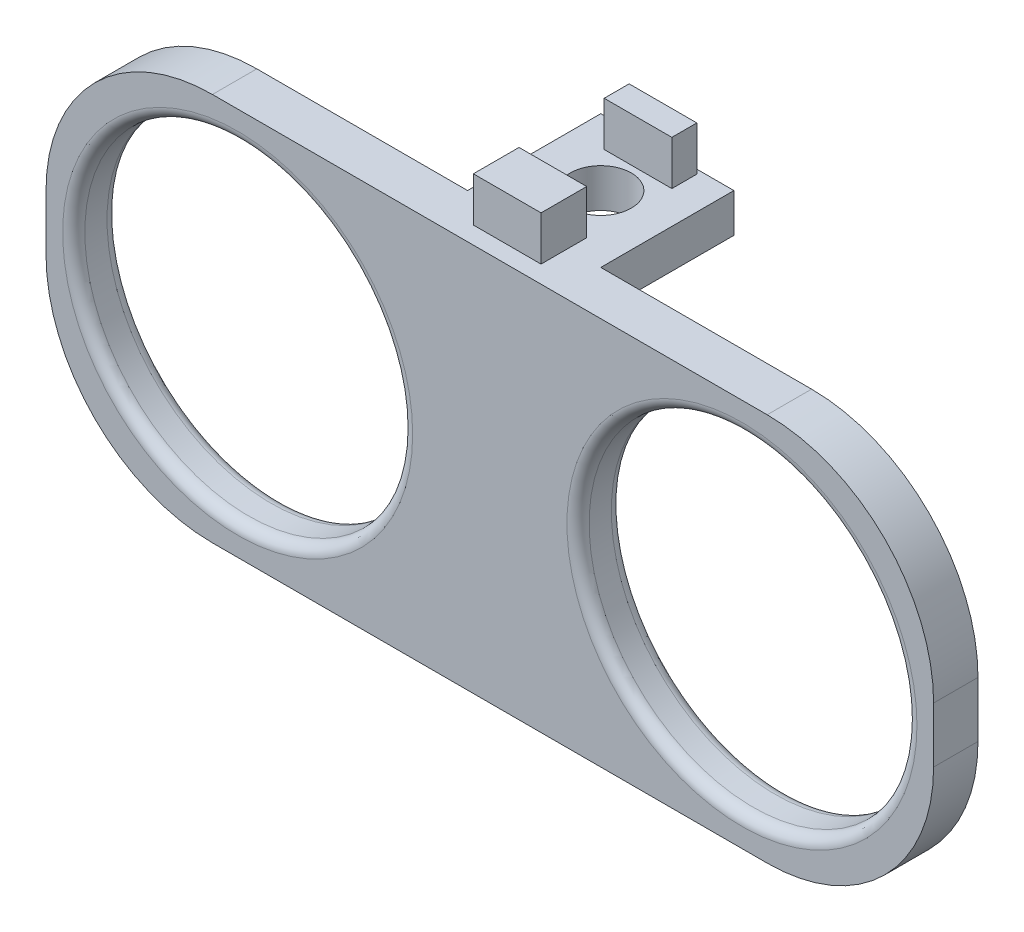
SolidWorks part; units mm, degrees
ref_plane "Front Plane" through (0, 0, 0) normal (0, 0, 1) x (1, 0, 0)
ref_plane "Top Plane" through (0, 0, 0) normal (0, 1, 0) x (1, 0, 0)
ref_plane "Right Plane" through (0, 0, 0) normal (1, 0, 0) x (0, 0, -1)
sketch "Sketch1" plane through (0, 0, 0) normal (0, 0, 1) x (1, 0, 0)
  line L1 (-40, 17.5) -> (40, 17.5)
  line L2 (-40, 17.5) -> (-40, -17.5)
  line L3 (-40, -17.5) -> (40, -17.5)
  line L4 (40, 17.5) -> (40, -17.5)
  line L5 (-40, 17.5) -> (40, -17.5) construction
  line L6 (-40, -17.5) -> (40, 17.5) construction
  point P0 (0, 0)
  dimension "D1" = 80
  dimension "D2" = 35
extrude "Boss-Extrude1" add sketch "Sketch1" along normal blind 4
sketch "Sketch2" plane through (0, 0, 4) normal (0, 0, 1) x (1, 0, 0)
  line L0 (40, 0) -> (37.5, 0)
  line L1 (40, -17.5) -> (40, 17.5) construction
  circle A0 centre (22.725, 0) radius 14.775
  dimension "D2" = 29.55
  dimension "D1" = 2.5
extrude "Cut-Extrude1" cut sketch "Sketch2" against normal blind 4 contours A0
ref_plane "Plane1" through (0, 0, 0) normal (1, 0, 0) x (0, 0, -1)
fillet "Fillet2" radius 15 2 edges at (-40, -17.5, 2) (40, -17.5, 2)
sketch "Sketch3" plane through (0, 0, 0) normal (0, 0, -1) x (-1, 0, 0)
  line L0 (0, 17.5) -> (0, 15.75)
  line L1 (-40, 17.5) -> (40, 17.5) construction
  line L3 (-6, 14) -> (6, 14)
  line L4 (-6, 14) -> (-6, 17.5)
  line L5 (-6, 17.5) -> (6, 17.5)
  line L6 (6, 14) -> (6, 17.5)
  line L7 (-6, 14) -> (6, 17.5) construction
  line L8 (-6, 17.5) -> (6, 14) construction
  dimension "D1" = 3.5
  dimension "D2" = 12
extrude "Boss-Extrude2" add sketch "Sketch3" along normal blind 12
sketch "Sketch4" plane through (0, 14, 0) normal (0, -1, 0) x (1, 0, 0)
  line L0 (-6, -12) -> (6, 0) construction
  line L1 (6, 0) -> (-6, 0) construction
  line L2 (6, -12) -> (-6, 0) construction
  line L3 (-6, -12) -> (-6, 0) construction
  circle A0 centre (0, -6) radius 2.75
  point P12 (0, -6)
  point P13 (6, 0)
  point P14 (0, 0)
  dimension "D1" = 5.5
extrude "Cut-Extrude2" cut sketch "Sketch4" against normal blind 5 contours A0
fillet "Fillet4" radius 1 2 edges at (37.5, 0, 0) (37.5, 0, 4)
mirror "Mirror4" about plane through (0, 0, 0) normal (1, 0, 0) of "Cut-Extrude1", "Fillet4"
fillet "Fillet5" radius 15 2 edges at (-40, 17.5, 2) (40, 17.5, 2)
sketch "Sketch6" plane through (0, 17.5, 0) normal (0, 1, 0) x (1, 0, 0)
  line L0 (0, 12) -> (0, 8.75) construction
  line L1 (-6, 12) -> (6, 12) construction
  line L2 (0, 3.25) -> (0, -4) construction
  line L4 (25, -4) -> (-25, -4) construction
  line L6 (-3.05, 11.6081) -> (3.05, 11.6081)
  line L7 (-3.05, 11.6081) -> (-3.05, 9.3578)
  line L8 (-3.05, 9.3578) -> (3.05, 9.3578)
  line L9 (3.05, 11.6081) -> (3.05, 9.3578)
  line L10 (-3.05, 11.6081) -> (3.05, 9.3578) construction
  line L11 (-3.05, 9.3578) -> (3.05, 11.6081) construction
  line L12 (-3.05, 1.6824) -> (3.05, 1.6824)
  line L13 (-3.05, 1.6824) -> (-3.05, -2.4324)
  line L14 (-3.05, -2.4324) -> (3.05, -2.4324)
  line L15 (3.05, 1.6824) -> (3.05, -2.4324)
  line L16 (-3.05, 1.6824) -> (3.05, -2.4324) construction
  line L17 (-3.05, -2.4324) -> (3.05, 1.6824) construction
  circle A0 centre (0, 6) radius 2.75 construction
  point P11 (0, 10.4829)
  point P16 (0, -0.375)
  dimension "D1" = 6.1
extrude "Boss-Extrude3" add sketch "Sketch6" along normal blind 4
